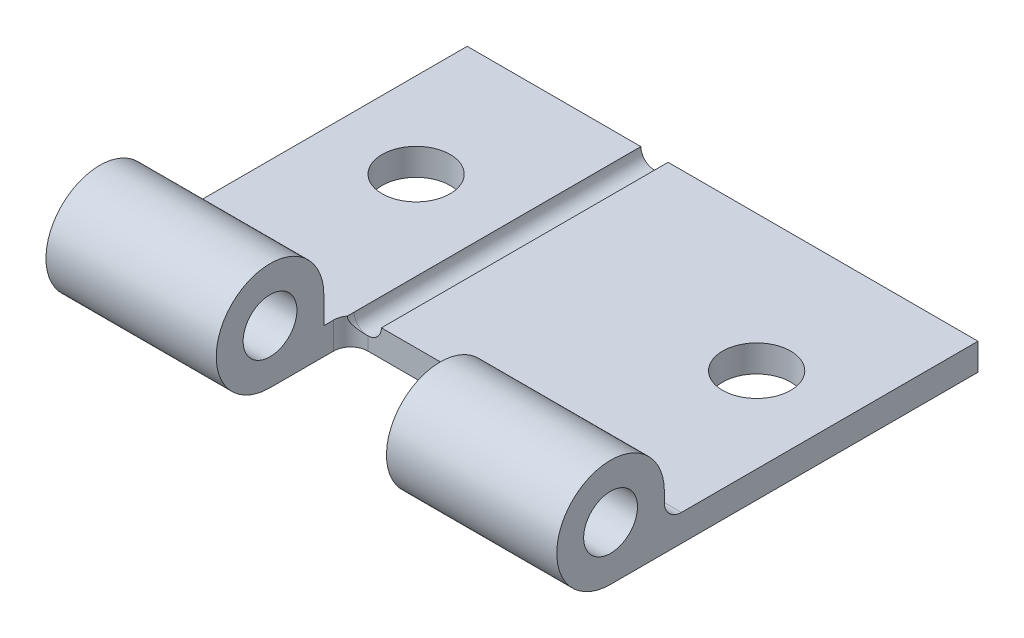
SolidWorks part; units mm, degrees
ref_plane "Front Plane" through (0, 0, 0) normal (0, 0, 1) x (1, 0, 0)
ref_plane "Top Plane" through (0, 0, 0) normal (0, 1, 0) x (1, 0, 0)
ref_plane "Right Plane" through (0, 0, 0) normal (1, 0, 0) x (0, 0, -1)
sketch "Sketch1" plane through (0, 0, 0) normal (0, 1, 0) x (1, 0, 0)
  line L1 (-7.7324, -4.7465) -> (17.2676, -4.7465)
  line L2 (-7.7324, -4.7465) -> (-7.7324, 5.2535)
  line L3 (-7.7324, 5.2535) -> (17.2676, 5.2535)
  line L4 (17.2676, -4.7465) -> (17.2676, 5.2535)
  dimension "D1" = 10
  dimension "D2" = 25
extrude "Base Plate" add sketch "Sketch1" along normal blind 0.79
ref_plane "Inner Plane" through (12.2676, 0, 0) normal (1, 0, 0) x (0, 0, -1)
ref_plane "Middle Plane" through (4.7676, 0, 0) normal (1, 0, 0) x (0, 0, -1)
sketch "Sketch5" plane through (12.2676, 0, 0) normal (1, 0, 0) x (0, 0, -1)
  line L0 (-7.9652, 0.79) -> (-4.7465, 0.79) construction
  line L1 (-3.9565, 1.58) -> (-3.9565, 0.79)
  line L2 (-5.5365, 0) -> (-4.7465, 0)
  arc A1 (-4.7465, 0.79) -> (-5.5365, 0) centre (-5.5365, 0.79) ccw construction
  arc A2 (-3.9565, 1.58) -> (-5.5365, 0) centre (-5.5365, 1.58) ccw
  circle A3 centre (-5.5365, 1.58) radius 0.79
  arc A4 (-4.7465, 0) -> (-3.9565, 0.79) centre (-4.7465, 0.79) ccw
  point P0 (-4.7465, 0)
  point P1 (-4.7465, 0.79)
  point P6 (-7.9652, 0.79)
extrude "Pin Holder" add sketch "Sketch5" against normal blind 5
fillet "Fillet1" radius 0.5 1 edges at (9.7676, 0.79, 3.9565)
sketch "Sketch6" plane through (0, 0.79, 0) normal (0, 1, 0) x (1, 0, 0)
  line L1 (17.2676, 5.2535) -> (-7.7324, 5.2535) construction
  line L2 (12.2676, -0.4345) -> (12.2676, 0.4345) construction
  circle A0 centre (9.7676, 1.2535) radius 1
  dimension "D3" = 2
  dimension "D1" = 2.5
  dimension "D2" = 4
extrude "Screw Holes" cut sketch "Sketch6" against normal blind 5
mirror "Mirror1" about plane through (4.7676, 0, 0) normal (1, 0, 0) of "Screw Holes", "Pin Holder"
sketch "Sketch7" plane through (0, 0, 4.7465) normal (0, 0, 1) x (1, 0, 0)
  line L0 (12.2676, 0.79) -> (12.2676, 0) construction
  line L1 (17.2676, 0) -> (12.2676, 0)
  line L2 (17.2676, 0) -> (17.2676, 0.79)
  line L3 (17.2676, 0.79) -> (12.2676, 0.79)
  line L4 (12.2676, 0) -> (12.2676, 0.79)
  line L6 (2.2676, 0.79) -> (7.2676, 0.79)
  line L7 (2.2676, 0.79) -> (2.2676, 0)
  line L8 (2.2676, 0) -> (7.2676, 0)
  line L9 (7.2676, 0.79) -> (7.2676, 0)
  line L10 (-7.7324, 0.79) -> (-2.7324, 0.79)
  line L11 (-7.7324, 0.79) -> (-7.7324, 0)
  line L12 (-7.7324, 0) -> (-2.7324, 0)
  line L13 (-2.7324, 0.79) -> (-2.7324, 0)
extrude "Hinge Grooves" cut sketch "Sketch7" against normal blind 1.58
fillet "Fillet2" radius 0.5 2 edges at (7.2676, 0.395, 3.1665) (2.2676, 0.395, 3.1665)
sketch "Sketch8" plane through (0, 0, -5.2535) normal (0, 0, -1) x (-1, 0, 0)
  line L2 (-2.7676, 0) -> (-2.7676, 0.79) construction
  line L3 (-17.2676, 0.79) -> (7.7324, 0.79) construction
  line L4 (7.7324, 0.79) -> (7.7324, 0) construction
  circle A1 centre (-2.7676, 0.79) radius 0.4
  point P7 (-2.7676, 0.79)
  point P8 (-2.7676, 0)
  dimension "D1" = 0.8
  dimension "D3" = 10.5
sketch "Sketch9" plane through (0, 0, 0) normal (0, -1, 0) x (1, 0, 0)
  line L0 (2.7676, -5.2535) -> (2.7676, 3.1665)
  line L2 (17.2676, -5.2535) -> (-7.7324, -5.2535) construction
  line L3 (-7.7324, 3.1665) -> (-2.7324, 3.1665) construction
  line L4 (-7.7324, -5.2535) -> (-7.7324, 3.1665) construction
  line L5 (2.7676, 3.1665) -> (2.7676, 3.8841)
  dimension "D1" = 10.5
sweep "Wire Groove" cut profiles "Sketch8" path "Sketch9"
sketch "Sketch10" plane through (-7.7324, 0, 0) normal (-1, 0, 0) x (0, 0, 1)
  line L1 (-5.2535, 0) -> (3.1665, 0)
  line L2 (-5.2535, 0) -> (-5.2535, 0.79)
  line L3 (-5.2535, 0.79) -> (3.1665, 0.79)
  line L4 (3.1665, 0) -> (3.1665, 0.79)
extrude "External Cutoff" cut sketch "Sketch10" against normal blind 5
sketch "Sketch11" plane through (17.2676, 0, 0) normal (1, 0, 0) x (0, 0, -1)
  line L1 (5.2535, 0) -> (-3.1665, 0)
  line L2 (5.2535, 0) -> (5.2535, 0.79)
  line L3 (5.2535, 0.79) -> (-3.1665, 0.79)
  line L4 (-3.1665, 0) -> (-3.1665, 0.79)
extrude "External Cutoff2" cut sketch "Sketch11" against normal blind 5
chamfer "Countersink" [suppressed] distance 1 angle 45
